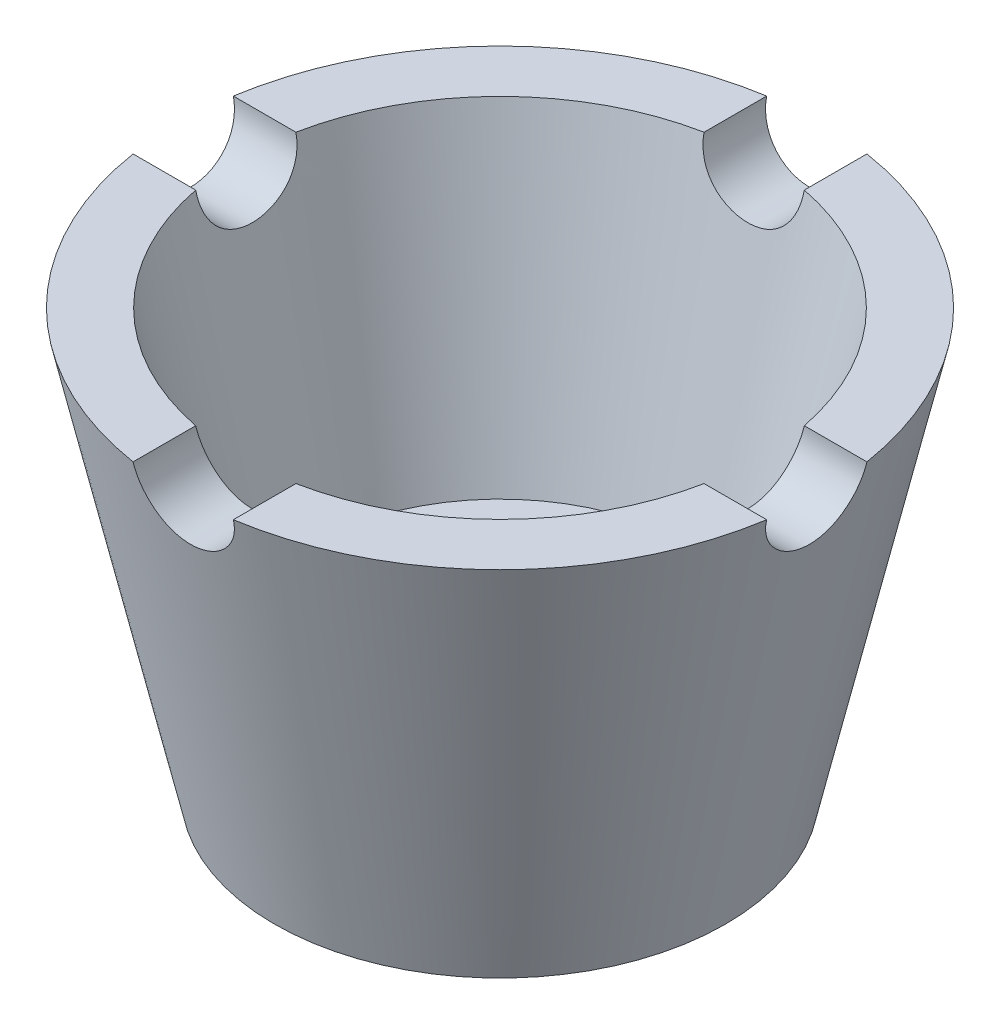
SolidWorks part; units mm, degrees
ref_plane "Front Plane" through (0, 0, 0) normal (0, 0, 1) x (1, 0, 0)
ref_plane "Top Plane" through (0, 0, 0) normal (0, 1, 0) x (1, 0, 0)
ref_plane "Right Plane" through (0, 0, 0) normal (1, 0, 0) x (0, 0, -1)
sketch "Sketch1" plane through (0, 0, 0) normal (0, 0, 1) x (1, 0, 0)
  line L0 (0, 0) -> (0, 34.7958) construction
  line L1 (11.25, 0) -> (22.5, 0)
  line L2 (22.5, 0) -> (32, 42)
  line L3 (32, 42) -> (25.8484, 42)
  line L4 (25.8484, 42) -> (19.0627, 12)
  line L5 (19.0627, 12) -> (11.25, 12)
  line L6 (11.25, 12) -> (11.25, 0)
  dimension "D1" = 45
  dimension "D2" = 64
  dimension "D3" = 42
  dimension "D4" = 12
  dimension "D5" = 6
  dimension "D6" = 22.5
revolve "Revolve1" add sketch "Sketch1" angle 360 about L0
sketch "Sketch2" plane through (0, 0, 0) normal (0, 0, 1) x (1, 0, 0)
  line L0 (32, 42) -> (-32, 42) construction
  line L1 (-5, 42) -> (5, 42)
  arc A0 (-5, 42) -> (5, 42) centre (0, 42) ccw
  dimension "D1" = 5
extrude "Cut-Extrude1" cut sketch "Sketch2" against normal up to next and the other way through all
pattern_circular "CirPattern1" count 4 over 360 about axis through (0, 42, 0) along (0, -1, 0) of "Cut-Extrude1"
